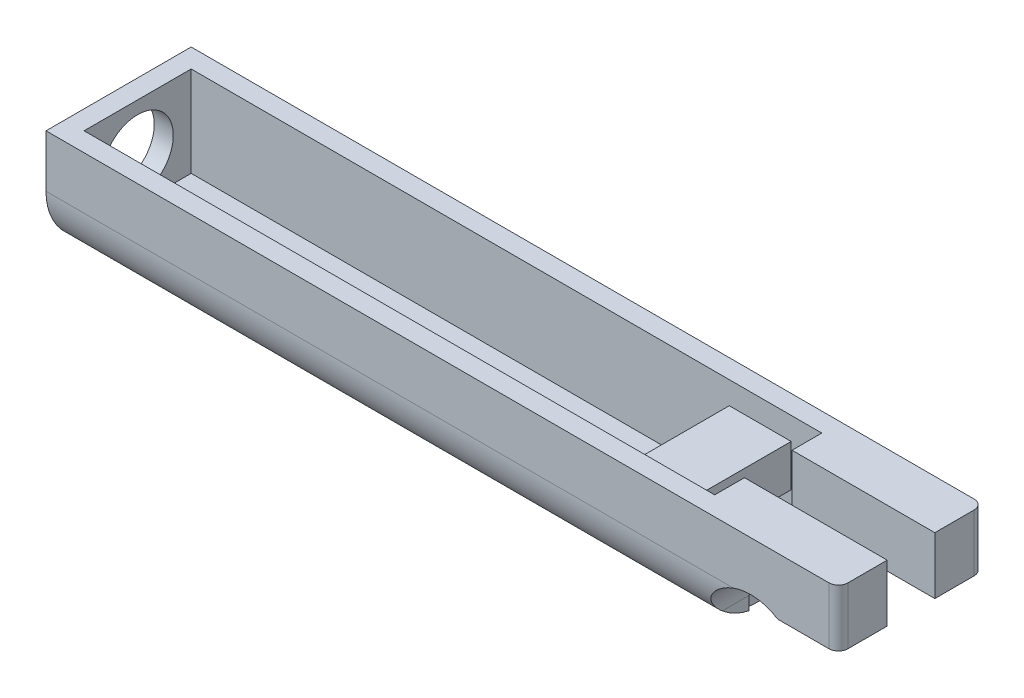
SolidWorks part; units mm, degrees
material "Plain Carbon Steel"
ref_plane "Front" through (0, 0, 0) normal (0, 0, 1) x (1, 0, 0)
ref_plane "Top" through (0, 0, 0) normal (0, 1, 0) x (1, 0, 0)
ref_plane "Right" through (0, 0, 0) normal (1, 0, 0) x (0, 0, -1)
sketch "Sketch1" plane through (0, 0, 0) normal (0, 1, 0) x (1, 0, 0)
  line L1 (-111.1902, -13.8988) -> (55.3098, -13.8988)
  line L2 (-111.1902, -13.8988) -> (-111.1902, -44.3988)
  line L3 (-111.1902, -44.3988) -> (55.3098, -44.3988)
  line L4 (55.3098, -13.8988) -> (55.3098, -44.3988)
  line L5 (-111.1902, -13.8988) -> (55.3098, -44.3988) construction
  line L6 (-111.1902, -44.3988) -> (55.3098, -13.8988) construction
  point P0 (-27.9402, -29.1488)
  dimension "D1" = 166.5
  dimension "D2" = 30.5
extrude "Boss-Extrude1" add sketch "Sketch1" along normal blind 24
sketch "Sketch2" plane through (0, 0, 0) normal (0, -1, 0) x (1, 0, 0)
  line L0 (55.3098, 44.3988) -> (55.3098, 13.8988) construction
  line L1 (25.3098, 34.1488) -> (55.3098, 34.1488)
  line L2 (25.3098, 34.1488) -> (25.3098, 24.1488)
  line L3 (25.3098, 24.1488) -> (55.3098, 24.1488)
  line L4 (55.3098, 34.1488) -> (55.3098, 24.1488)
  line L5 (25.3098, 34.1488) -> (55.3098, 24.1488) construction
  line L6 (25.3098, 24.1488) -> (55.3098, 34.1488) construction
  point P0 (40.3098, 29.1488)
  dimension "D1" = 10
  dimension "D2" = 30
  dimension "D3" = 10.25
extrude "Cut-Extrude1" cut sketch "Sketch2" against normal through all
sketch "Sketch4" plane through (0, 0, 13.8988) normal (0, 0, -1) x (-1, 0, 0)
  line L0 (-26.3152, 3.0974) -> (-26.3152, 0)
  line L1 (-42.5214, 12) -> (-55.3098, 12)
  line L2 (-55.3098, 24) -> (-55.3098, 0) construction
  line L3 (-26.3152, 0) -> (-55.3098, 0)
  line L4 (-55.3098, 0) -> (-55.3098, 12)
  arc A1 (-26.3152, 3.0974) -> (-42.5214, 12) centre (-36.8635, 3.0974) ccw
extrude "Cut-Extrude2" cut sketch "Sketch4" against normal through all
fillet "Fillet1" radius 2 2 edges at (55.3098, 18, 13.8988) (55.3098, 18, 44.3988)
fillet "Fillet2" radius 13 2 edges at (-42.4375, 0, 44.3988) (-42.4375, 0, 13.8988)
sketch "Sketch5" plane through (0, 24, 0) normal (0, 1, 0) x (1, 0, 0)
  line L0 (25.3098, -13.8988) -> (25.3098, -44.3988) construction
  line L1 (53.3098, -13.8988) -> (-111.1902, -13.8988) construction
  line L2 (-111.1902, -44.3988) -> (53.3098, -44.3988) construction
  line L3 (25.3098, -34.1488) -> (25.3098, -24.1488) construction
  line L4 (-111.1902, -13.8988) -> (-111.1902, -44.3988) construction
  line L5 (25.3098, -40.3988) -> (-107.1902, -40.3988)
  line L6 (25.3098, -40.3988) -> (25.3098, -17.8988)
  line L7 (25.3098, -17.8988) -> (-107.1902, -17.8988)
  line L8 (-107.1902, -40.3988) -> (-107.1902, -17.8988)
  dimension "D1" = 4
  dimension "D2" = 4
  dimension "D3" = 4
extrude "Cut-Extrude3" cut sketch "Sketch5" against normal blind 19
sketch "Sketch6" plane through (-111.1902, 0, 0) normal (-1, 0, 0) x (0, 0, 1)
  line L0 (29.1488, 0) -> (29.1488, 24) construction
  line L1 (26.8988, 0) -> (31.3988, 0) construction
  line L2 (13.8988, 24) -> (44.3988, 24) construction
  circle A0 centre (29.1488, 13.8) radius 7.5
  dimension "D1" = 15
  dimension "D2" = 10.2
extrude "Cut-Extrude4" cut sketch "Sketch6" against normal blind 4
sketch "Sketch7" plane through (0, 0, 40.3988) normal (0, 0, -1) x (-1, 0, 0)
  line L1 (-5.877, 10.4574) -> (-18.877, 10.4574)
  line L2 (-5.877, 10.4574) -> (-5.877, 19.2574)
  line L3 (-5.877, 19.2574) -> (-18.877, 19.2574)
  line L4 (-18.877, 10.4574) -> (-18.877, 19.2574)
  dimension "D1" = 8.8
  dimension "D2" = 13
extrude "Boss-Extrude2" add sketch "Sketch7" along normal blind 22.5
sketch "Sketch8" plane through (18.877, 0, 0) normal (1, 0, 0) x (0, 0, -1)
  circle A0 centre (-29.1488, 13.8) radius 2
  dimension "D1" = 4
extrude "Cut-Extrude5" cut sketch "Sketch8" against normal blind 13
